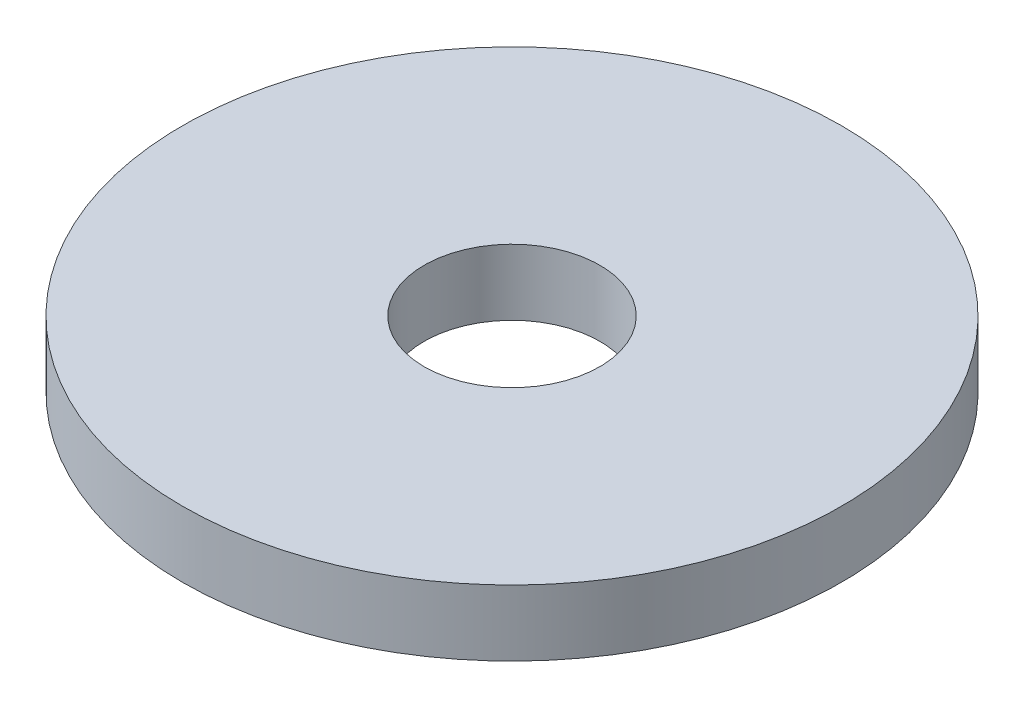
SolidWorks part; units mm, degrees
material "AISI 1020"
ref_plane "Alzado" through (0, 0, 0) normal (0, 0, 1) x (1, 0, 0)
ref_plane "Planta" through (0, 0, 0) normal (0, 1, 0) x (1, 0, 0)
ref_plane "Vista lateral" through (0, 0, 0) normal (1, 0, 0) x (0, 0, -1)
sketch "Croquis1" plane through (0, 0, 0) normal (0, 0, 1) x (1, 0, 0)
  line L0 (0, 3) -> (0, -2.0705) construction
  line L2 (0, 0) -> (15, 0)
  line L5 (0, -55) -> (0, 55) construction
  line L6 (15, 0) -> (15, 3)
  line L7 (15, 3) -> (0, 3)
  dimension "D1" = 30
  dimension "D2" = 3
revolve "Revolución3" add sketch "Croquis1" angle 360 about L0
sketch "Croquis5" plane through (0, 3, 0) normal (0, 1, 0) x (1, 0, 0)
  circle A0 centre (0, 0) radius 4
  dimension "D1" = 8
extrude "Cortar-Extruir1" cut sketch "Croquis5" against normal blind 10
